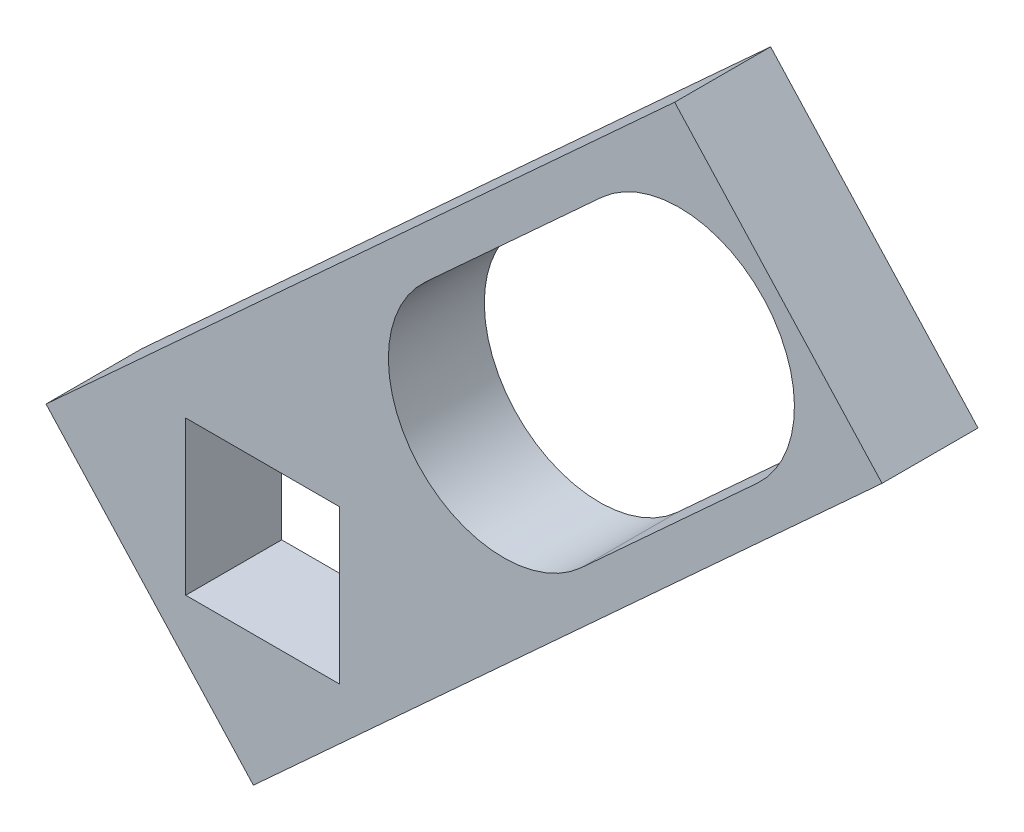
SolidWorks part; units mm, degrees
ref_plane "Front Plane" through (0, 0, 0) normal (0, 0, 1) x (1, 0, 0)
ref_plane "Top Plane" through (0, 0, 0) normal (0, 1, 0) x (1, 0, 0)
ref_plane "Right Plane" through (0, 0, 0) normal (1, 0, 0) x (0, 0, -1)
sketch "Sketch1" plane through (0, 0, 0) normal (0, 0, 1) x (1, 0, 0)
  line L0 (0, 0) -> (16.3794, 15)
  line L5 (0, 0) -> (-5.403, 5.8998)
  line L6 (16.3794, 15) -> (10.9764, 20.8998)
  line L7 (-5.403, 5.8998) -> (10.9764, 20.8998)
  dimension "D1" = 22.21
  dimension "D2" = 8
  dimension "D3" = 15
extrude "Boss-Extrude1" add sketch "Sketch1" along normal blind 2.5 contours L7 L6 L0 L5
sketch "Sketch2" plane through (0, 0, 2.5) normal (0, 0, 1) x (1, 0, 0)
  line L0 (0, 0) -> (16.3794, 15) construction
  line L1 (-1.7624, 7.4051) -> (2.2376, 7.4051)
  line L2 (-1.7624, 7.4051) -> (-1.7624, 3.4051)
  line L3 (-1.7624, 3.4051) -> (2.2376, 3.4051)
  line L4 (2.2376, 7.4051) -> (2.2376, 3.4051)
  line L5 (0, 0) -> (-5.403, 5.8998) construction
  dimension "D1" = 4
  dimension "D2" = 4
  dimension "D3" = 1
  dimension "D4" = 1
extrude "Cut-Extrude1" cut sketch "Sketch2" against normal through all
sketch "Sketch3" plane through (0, 0, 2.5) normal (0, 0, 1) x (1, 0, 0)
  line L0 (11.0967, 15.5861) -> (6.517, 11.3921) construction
  line L1 (13.1228, 13.3737) -> (8.5431, 9.1796)
  line L2 (9.0706, 17.7985) -> (4.4909, 13.6045)
  line L3 (0, 0) -> (16.3794, 15) construction
  line L4 (16.3794, 15) -> (10.9764, 20.8998) construction
  line L5 (-5.403, 5.8998) -> (10.9764, 20.8998) construction
  arc A0 (13.1228, 13.3737) -> (9.0706, 17.7985) centre (11.0967, 15.5861) ccw
  arc A1 (4.4909, 13.6045) -> (8.5431, 9.1796) centre (6.517, 11.3921) ccw
  point P2 (8.8069, 13.4891)
  dimension "D1" = 0
  dimension "D2" = 3.5
  dimension "D3" = 4
extrude "Cut-Extrude2" cut sketch "Sketch3" against normal through all
